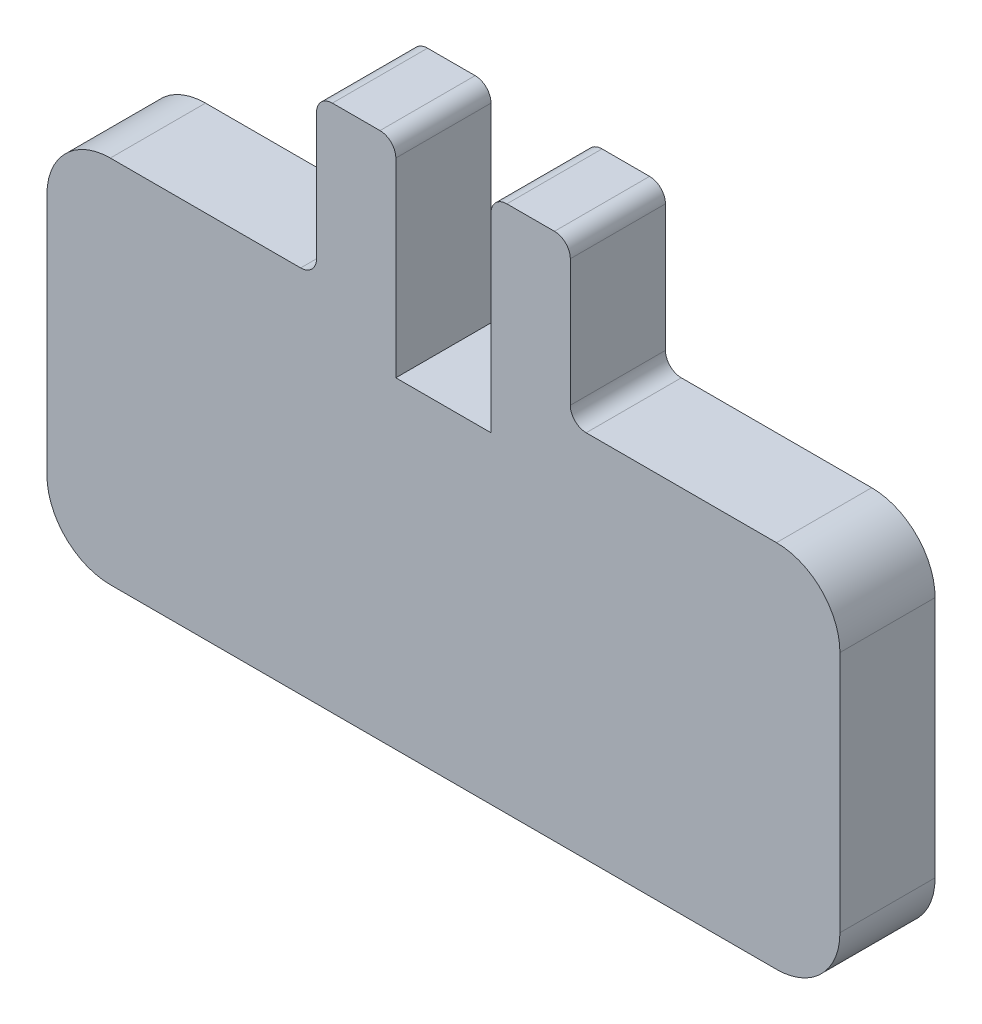
SolidWorks part; units mm, degrees
ref_plane "Plan de face" through (0, 0, 0) normal (0, 0, 1) x (1, 0, 0)
ref_plane "Plan de dessus" through (0, 0, 0) normal (0, 1, 0) x (1, 0, 0)
ref_plane "Plan de droite" through (0, 0, 0) normal (1, 0, 0) x (0, 0, -1)
sketch "Esquisse1" plane through (0, 0, 0) normal (0, 0, 1) x (1, 0, 0)
  line L1 (0, 0) -> (50, 0)
  line L2 (0, 0) -> (0, 44)
  line L3 (0, 44) -> (50, 44)
  line L4 (50, 0) -> (50, 44)
  dimension "D1" = 50
  dimension "D2" = 44
extrude "Boss.-Extru.1" add sketch "Esquisse1" along normal blind 6
sketch "Esquisse2" plane through (0, 0, 6) normal (0, 0, 1) x (1, 0, 0)
  line L0 (50, 44) -> (0, 44) construction
  line L1 (22, 44) -> (28, 44)
  line L2 (22, 44) -> (22, 20.3)
  line L3 (22, 20.3) -> (28, 20.3)
  line L4 (28, 44) -> (28, 20.3)
  line L5 (50, 0) -> (50, 44) construction
  line L7 (0, 0) -> (50, 0) construction
  line L9 (50, 44) -> (33, 44)
  line L10 (50, 44) -> (50, 23.3)
  line L11 (50, 23.3) -> (33, 23.3)
  line L12 (33, 44) -> (33, 23.3)
  line L13 (0, 44) -> (17, 44)
  line L14 (0, 44) -> (0, 23.3)
  line L15 (0, 23.3) -> (17, 23.3)
  line L16 (17, 44) -> (17, 23.3)
  dimension "D1" = 6
  dimension "D2" = 22
  dimension "D3" = 20.3
  dimension "D4" = 3
  dimension "D5" = 3
  dimension "D6" = 5
  dimension "D7" = 5
extrude "Enlèv. mat.-Extru.1" cut sketch "Esquisse2" against normal blind 6
sketch "Esquisse3" plane through (0, 0, 6) normal (0, 0, 1) x (1, 0, 0)
  line L0 (22, 44) -> (22, 20.3) construction
  line L1 (17, 44) -> (22, 44)
  line L2 (17, 44) -> (17, 33.3)
  line L3 (17, 33.3) -> (22, 33.3)
  line L4 (22, 44) -> (22, 33.3)
  line L5 (33, 44) -> (33, 23.3) construction
  line L6 (28, 44) -> (33, 44)
  line L7 (28, 44) -> (28, 33.3)
  line L8 (28, 33.3) -> (33, 33.3)
  line L9 (33, 44) -> (33, 33.3)
  dimension "D1" = 10.7
  dimension "D2" = 10.7
extrude "Enlèv. mat.-Extru.2" cut sketch "Esquisse3" against normal blind 6
fillet "Congé1" radius 4 4 edges at (50, 23.3, 3) (50, 0, 3) (0, 23.3, 3) (0, 0, 3)
fillet "Congé2" radius 1 6 edges at (33, 23.3, 3) (17, 23.3, 3) (33, 33.3, 3) (28, 33.3, 3) (22, 33.3, 3) (17, 33.3, 3)
